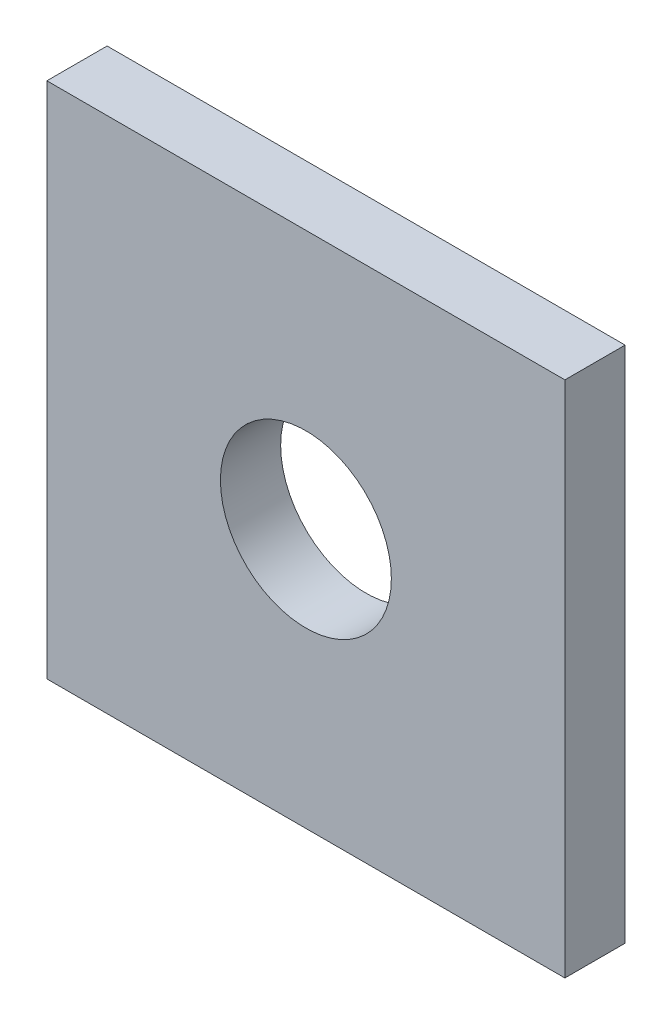
SolidWorks part; units mm, degrees
ref_plane "Alzado" through (0, 0, 0) normal (0, 0, 1) x (1, 0, 0)
ref_plane "Planta" through (0, 0, 0) normal (0, 1, 0) x (1, 0, 0)
ref_plane "Vista lateral" through (0, 0, 0) normal (1, 0, 0) x (0, 0, -1)
sketch "Croquis1" plane through (0, 0, 0) normal (0, 0, 1) x (1, 0, 0)
  line L1 (43, -43) -> (-43, -43)
  line L2 (43, -43) -> (43, 43)
  line L3 (43, 43) -> (-43, 43)
  line L4 (-43, -43) -> (-43, 43)
  line L5 (43, -43) -> (-43, 43) construction
  line L6 (43, 43) -> (-43, -43) construction
  circle A0 centre (0, 0) radius 14.1897
  point P0 (0, 0)
  dimension "D1" = 86
  dimension "D2" = 86
extrude "Saliente-Extruir1" add sketch "Croquis1" along normal blind 10
